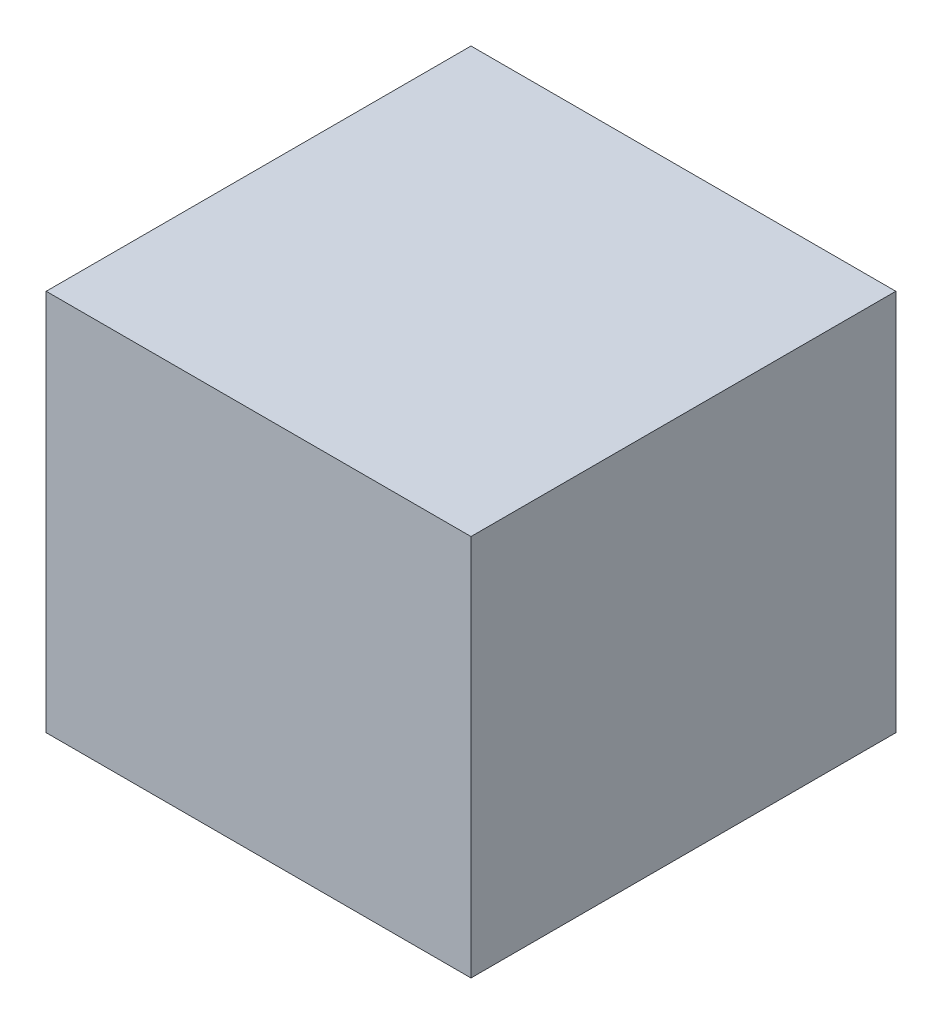
SolidWorks part; units mm, degrees
ref_plane "Front Plane" through (0, 0, 0) normal (0, 0, 1) x (1, 0, 0)
ref_plane "Top Plane" through (0, 0, 0) normal (0, 1, 0) x (1, 0, 0)
ref_plane "Right Plane" through (0, 0, 0) normal (1, 0, 0) x (0, 0, -1)
sketch "Sketch1" plane through (0, 0, 0) normal (0, 1, 0) x (1, 0, 0)
  line L1 (-63.5, -63.5) -> (63.5, -63.5)
  line L2 (-63.5, -63.5) -> (-63.5, 63.5)
  line L3 (-63.5, 63.5) -> (63.5, 63.5)
  line L4 (63.5, -63.5) -> (63.5, 63.5)
  line L5 (-63.5, -63.5) -> (63.5, 63.5) construction
  line L6 (-63.5, 63.5) -> (63.5, -63.5) construction
  point P0 (0, 0)
  dimension "D1" = 127
  dimension "D2" = 127
extrude "Boss-Extrude1" add sketch "Sketch1" along normal blind 114.3
